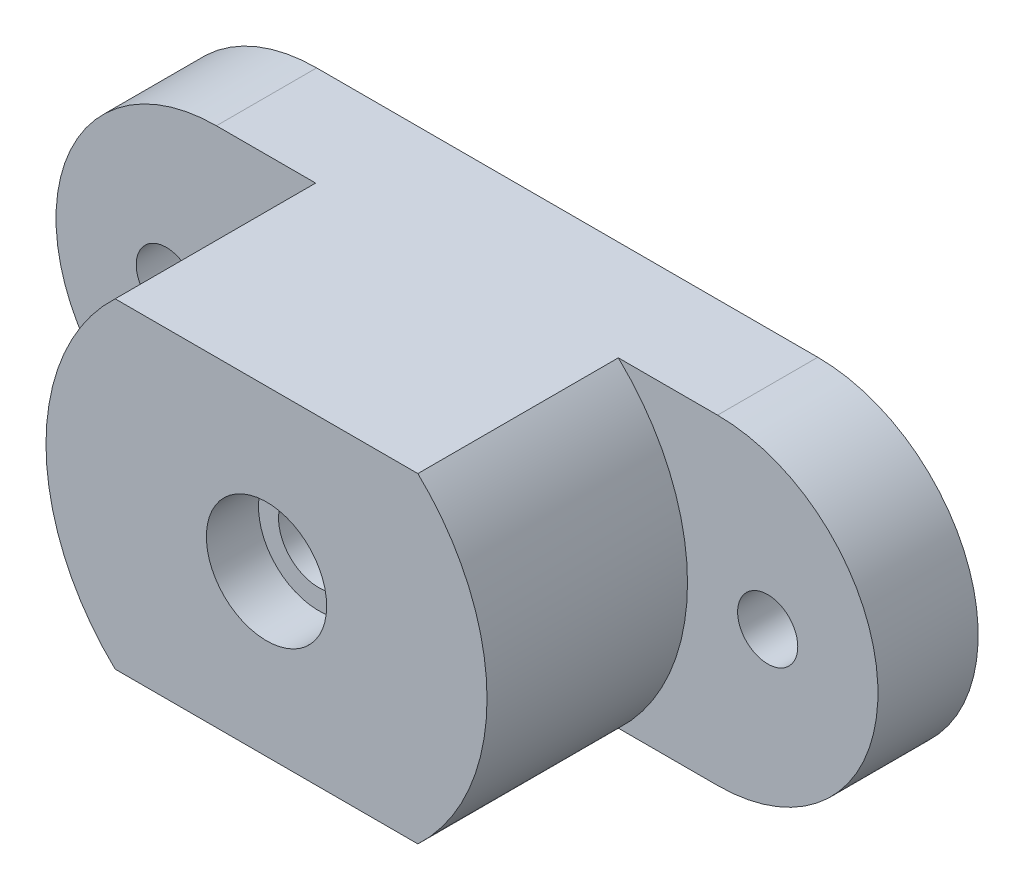
SolidWorks part; units mm, degrees
ref_plane "前视基准面" through (0, 0, 0) normal (0, 0, 1) x (1, 0, 0)
ref_plane "上视基准面" through (0, 0, 0) normal (0, 1, 0) x (1, 0, 0)
ref_plane "右视基准面" through (0, 0, 0) normal (1, 0, 0) x (0, 0, -1)
other "Configuration Table"
sketch "草图1" plane through (0, 0, 0) normal (0, 0, 1) x (1, 0, 0)
  line L0 (0, 0) -> (25, 0) construction
  line L1 (0, 8) -> (25, 8)
  line L2 (0, -8) -> (25, -8)
  arc A0 (0, 8) -> (0, -8) centre (0, 0) ccw
  arc A1 (25, -8) -> (25, 8) centre (25, 0) ccw
  point P3 (12.5, 0)
  dimension "D2" = 8
  dimension "D1" = 25
extrude "凸台-拉伸1" add sketch "草图1" along normal blind 5
sketch "草图2" plane through (0, 0, 5) normal (0, 0, 1) x (1, 0, 0)
  line L3 (0, -8) -> (25, -8)
  line L4 (25, 8) -> (0, 8)
  line L5 (4.9502, -8) -> (20.0498, -8)
  line L6 (20.0498, 8) -> (4.9502, 8)
  arc A1 (4.9502, 8) -> (4.9502, -8) centre (12.5, 0) ccw
  arc A2 (20.0498, -8) -> (20.0498, 8) centre (12.5, 0) ccw
  arc A4 (0, 8) -> (0, -8) centre (0, 0) ccw
  arc A5 (25, -8) -> (25, 8) centre (25, 0) ccw
  dimension "D1" = 22
  dimension "D2" = 0
  dimension "D3" = 12.5
  dimension "D4" = 8
extrude "凸台-拉伸2" add sketch "草图2" along normal blind 10
sketch "草图3" plane through (0, 0, 15) normal (0, 0, 1) x (1, 0, 0)
  circle A0 centre (12.5, 0) radius 3
  dimension "D1" = 6
extrude "切除-拉伸1" cut sketch "草图3" against normal blind 2.6
sketch "草图4" plane through (0, 0, 12.4) normal (0, 0, 1) x (1, 0, 0)
  circle A0 centre (12.5, 0) radius 2
  dimension "D1" = 4
extrude "切除-拉伸2" cut sketch "草图4" against normal through all
sketch "草图5" plane through (0, 0, 0) normal (0, 0, -1) x (-1, 0, 0)
  circle A0 centre (-12.5, 0) radius 6
  dimension "D1" = 12
extrude "切除-拉伸3" cut sketch "草图5" against normal blind 10
sketch "草图6" plane through (0, 0, 5) normal (0, 0, 1) x (1, 0, 0)
  line L1 (4.9502, 8) -> (0, 8) construction
  circle A0 centre (-2.5, 0) radius 1.5
  circle A1 centre (27.5, 0) radius 1.5
  arc A4 (0, 8) -> (0, -8) centre (0, 0) ccw construction
  point P11 (-8, 0)
  dimension "D1" = 3
  dimension "D2" = 3
  dimension "D3" = 8
  dimension "D4" = 30
  dimension "D5" = 5.5
extrude "切除-拉伸4" cut sketch "草图6" against normal through all
